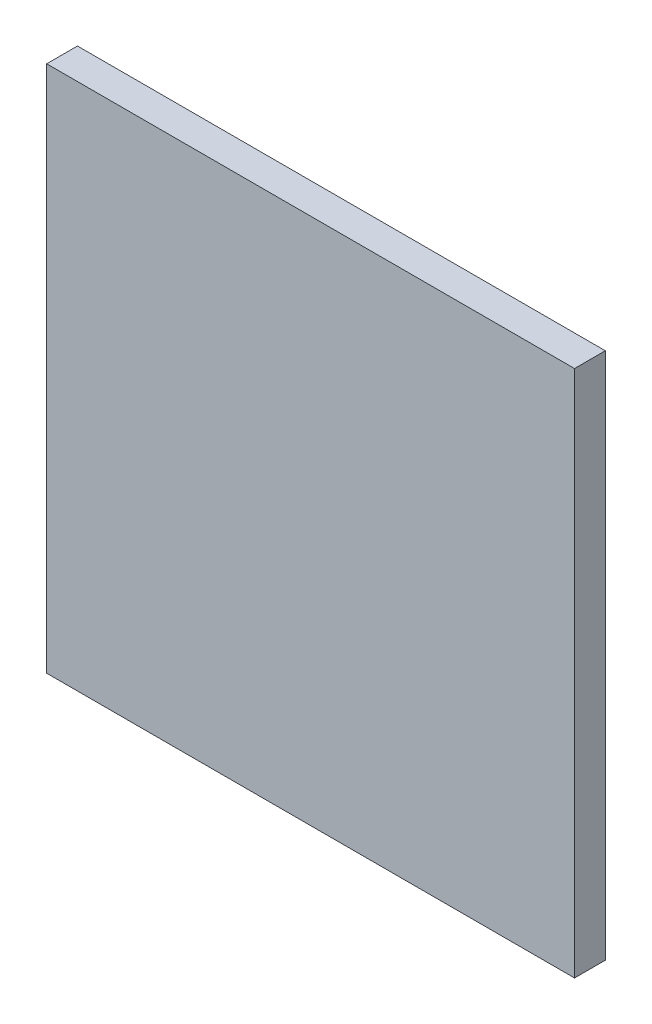
SolidWorks part; units mm, degrees
ref_plane "Front Plane" through (0, 0, 0) normal (0, 0, 1) x (1, 0, 0)
ref_plane "Top Plane" through (0, 0, 0) normal (0, 1, 0) x (1, 0, 0)
ref_plane "Right Plane" through (0, 0, 0) normal (1, 0, 0) x (0, 0, -1)
sketch "Sketch1" plane through (0, 0, 0) normal (0, 0, 1) x (1, 0, 0)
  line L1 (-47.625, -47.625) -> (47.625, -47.625)
  line L2 (-47.625, -47.625) -> (-47.625, 47.625)
  line L3 (-47.625, 47.625) -> (47.625, 47.625)
  line L4 (47.625, -47.625) -> (47.625, 47.625)
  line L5 (-47.625, -47.625) -> (47.625, 47.625) construction
  line L6 (-47.625, 47.625) -> (47.625, -47.625) construction
  point P0 (0, 0)
  dimension "D1" = 95.25
extrude "Boss-Extrude1" add sketch "Sketch1" along normal blind 5.5562
sketch "Sketch2" plane through (0, 0, 0) normal (0, 0, -1) x (-1, 0, 0)
  line L0 (47.625, 47.625) -> (47.625, -47.625) construction
  line L1 (-37.973, -37.973) -> (37.973, -37.973) construction
  line L2 (-37.973, -37.973) -> (-37.973, 37.973) construction
  line L3 (-37.973, 37.973) -> (37.973, 37.973) construction
  line L4 (37.973, -37.973) -> (37.973, 37.973) construction
  line L5 (-37.973, -37.973) -> (37.973, 37.973) construction
  line L6 (-37.973, 37.973) -> (37.973, -37.973) construction
  point P0 (0, 0)
  dimension "D1" = 9.652
